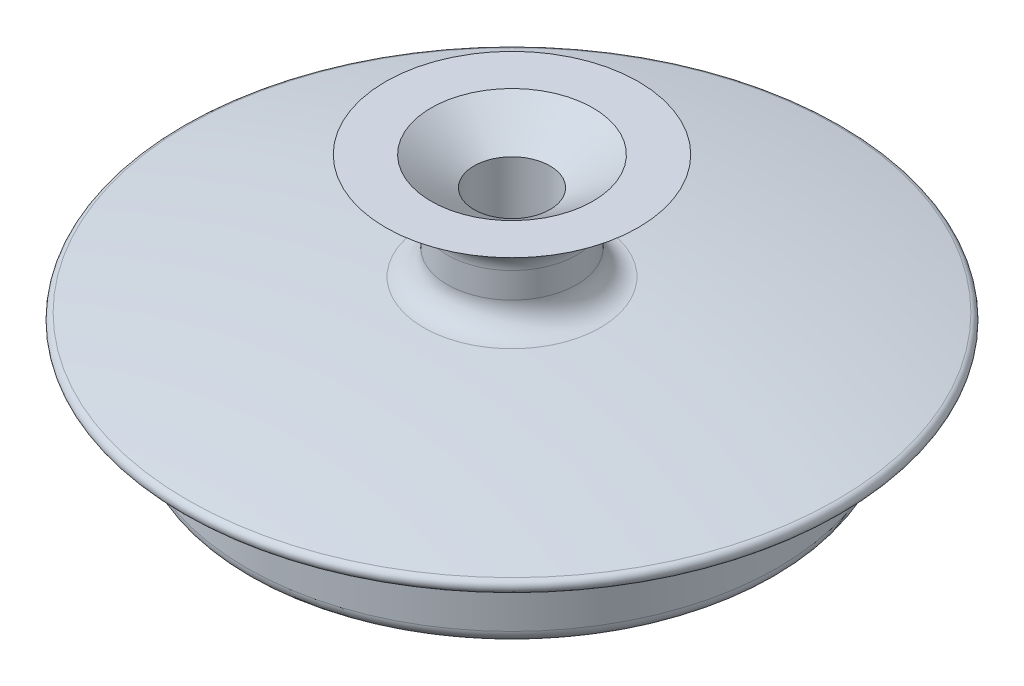
SolidWorks part; units mm, degrees
material "玻璃"
ref_plane "前视基准面" through (0, 0, 0) normal (0, 0, 1) x (1, 0, 0)
ref_plane "上视基准面" through (0, 0, 0) normal (0, 1, 0) x (1, 0, 0)
ref_plane "右视基准面" through (0, 0, 0) normal (1, 0, 0) x (0, 0, -1)
other "Configuration Table"
sketch "草图1" plane through (0, 0, 0) normal (0, 0, 1) x (1, 0, 0)
  line L0 (0, -871.5153) -> (0, 0) construction
  line L3 (-19, -1.8216) -> (-19, -7.8216)
  line L5 (-21, -7.8216) -> (-21, -1.8216)
  line L9 (-30, -1.8216) -> (-21, -1.8216)
  line L11 (-5.1032, 1.7276) -> (-5.1032, 6.7276)
  line L12 (-5.1032, 6.7276) -> (-10, 10)
  line L13 (-10, 10) -> (-6.4004, 10)
  line L14 (-6.4004, 10) -> (-3, 7.7276)
  line L15 (-3, 7.7276) -> (-3, -0.045)
  line L16 (0, 9.2809) -> (0, 42704.2511) construction
  arc A0 (-3, -0.045) -> (-19, -1.8216) centre (0, -100) ccw
  arc A2 (-5.1032, 1.7276) -> (-30, -1.8216) centre (0, -123.1682) ccw
  arc A3 (-21, -7.8216) -> (-19, -7.8216) centre (-20, -7.8216) ccw
  point P6 (-18.7911, -9.7725)
  point P11 (0, 0)
  point P21 (0, 0)
  dimension "D1" = 200
  dimension "D7" = 10
  dimension "D5" = 250
  dimension "D2" = 2
  dimension "D3" = 2
  dimension "D4" = 60
  dimension "D6" = 5
  dimension "D8" = 42
  dimension "D9" = 1
  dimension "D10" = 10
  dimension "D11" = 3
  dimension "D12" = 6
revolve "旋转1" add sketch "草图1" angle 360 about L0
fillet "圆角1" radius 0.5 1 edges at (30, -1.8216, 0)
fillet "圆角2" radius 2 2 edges at (5.1032, 6.7276, 0) (5.1032, 1.7276, 0)
